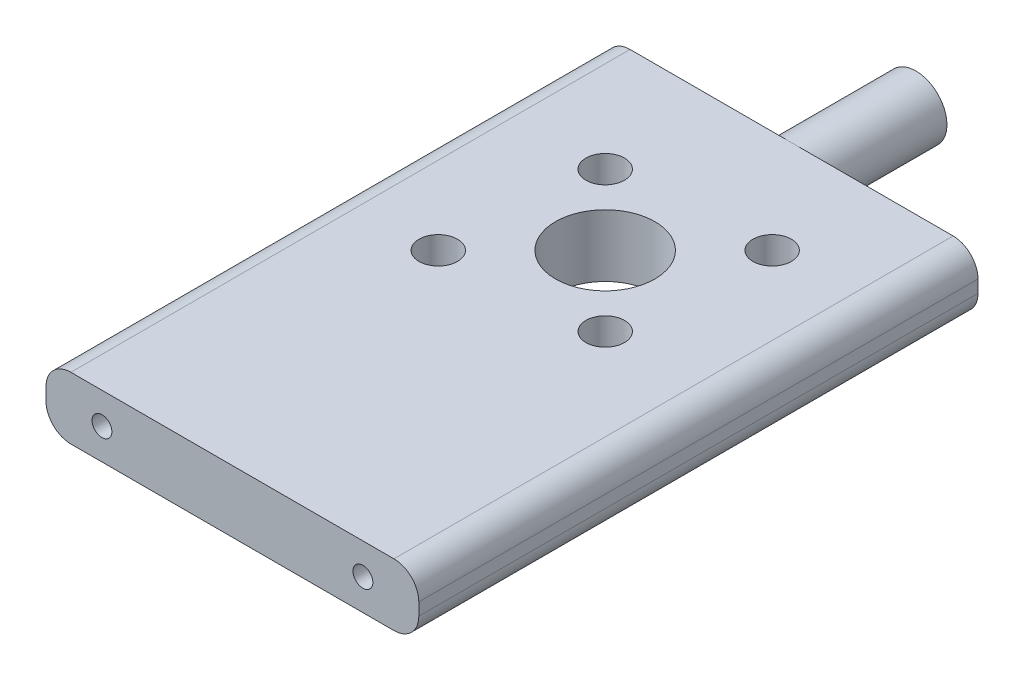
SolidWorks part; units mm, degrees
ref_plane "Front Plane" through (0, 0, 0) normal (0, 0, 1) x (1, 0, 0)
ref_plane "Top Plane" through (0, 0, 0) normal (0, 1, 0) x (1, 0, 0)
ref_plane "Right Plane" through (0, 0, 0) normal (1, 0, 0) x (0, 0, -1)
sketch "Sketch1" plane through (0, 0, 0) normal (0, 1, 0) x (1, 0, 0)
  line L1 (22.6874, -18.8055) -> (-7.3126, -18.8055)
  line L2 (22.6874, -18.8055) -> (22.6874, 26.1945)
  line L3 (22.6874, 26.1945) -> (-7.3126, 26.1945)
  line L4 (-7.3126, -18.8055) -> (-7.3126, 26.1945)
  dimension "D1" = 30
  dimension "D2" = 45
extrude "Boss-Extrude1" add sketch "Sketch1" along normal blind 5
sketch "Sketch2" plane through (0, 5, 0) normal (0, 1, 0) x (-1, 0, 0)
  line L0 (-22.6874, -26.1945) -> (7.3126, -26.1945) construction
  line L1 (-22.6874, 18.8055) -> (-22.6874, -26.1945) construction
  circle A0 centre (-7.6874, -11.1945) radius 4
  dimension "D1" = 8
  dimension "D2" = 15
  dimension "D3" = 15
extrude "Cut-Extrude1" cut sketch "Sketch2" against normal blind 5
sketch "Sketch3" plane through (0, 5, 0) normal (0, 1, 0) x (1, 0, 0)
  line L0 (22.6874, -18.8055) -> (22.6874, 26.1945) construction
  line L1 (22.6874, 26.1945) -> (-7.3126, 26.1945) construction
  circle A0 centre (2.0306, 16.8513) radius 1.55
  circle A1 centre (14.4049, 17.912) radius 1.55
  circle A2 centre (13.3443, 5.5376) radius 1.55
  circle A3 centre (0.9699, 4.477) radius 1.55
  point P8 (7.6874, 11.1945)
  dimension "D1" = 3.1
  dimension "D2" = 3.1
  dimension "D3" = 3.1
  dimension "D4" = 3.1
  dimension "D5" = 19
  dimension "D6" = 16
  dimension "D7" = 9.5
  dimension "D8" = 8
  dimension "D9" = 15
  dimension "D10" = 15
extrude "Cut-Extrude2" cut sketch "Sketch3" against normal blind 5
sketch "Sketch4" plane through (0, 0, 18.8055) normal (0, 0, 1) x (1, 0, 0)
  line L0 (-7.3126, 5) -> (22.6874, 5) construction
  line L1 (-7.3126, 5) -> (-7.3126, 0) construction
  circle A0 centre (-2.8126, 2.5) radius 0.8
  circle A1 centre (18.1874, 2.5) radius 0.8
  dimension "D1" = 1.6
  dimension "D2" = 1.6
  dimension "D3" = 2.5
  dimension "D4" = 2.5
  dimension "D5" = 21
  dimension "D6" = 4.5
extrude "Cut-Extrude3" cut sketch "Sketch4" against normal blind 5
sketch "Sketch5" plane through (0, 0, -26.1945) normal (0, 0, -1) x (-1, 0, 0)
  line L0 (-22.6874, 0) -> (7.3126, 0) construction
  line L1 (-22.6874, 5) -> (-22.6874, 0) construction
  circle A0 centre (-7.6874, 2.5) radius 2.5
  dimension "D1" = 5
  dimension "D2" = 2.5
  dimension "D3" = 15
extrude "Boss-Extrude2" add sketch "Sketch5" along normal blind 10
fillet "Fillet1" radius 2 4 edges at (22.6874, 0, -3.6945) (-7.3126, 0, -3.6945) (22.6874, 5, -3.6945) (-7.3126, 5, -3.6945)
